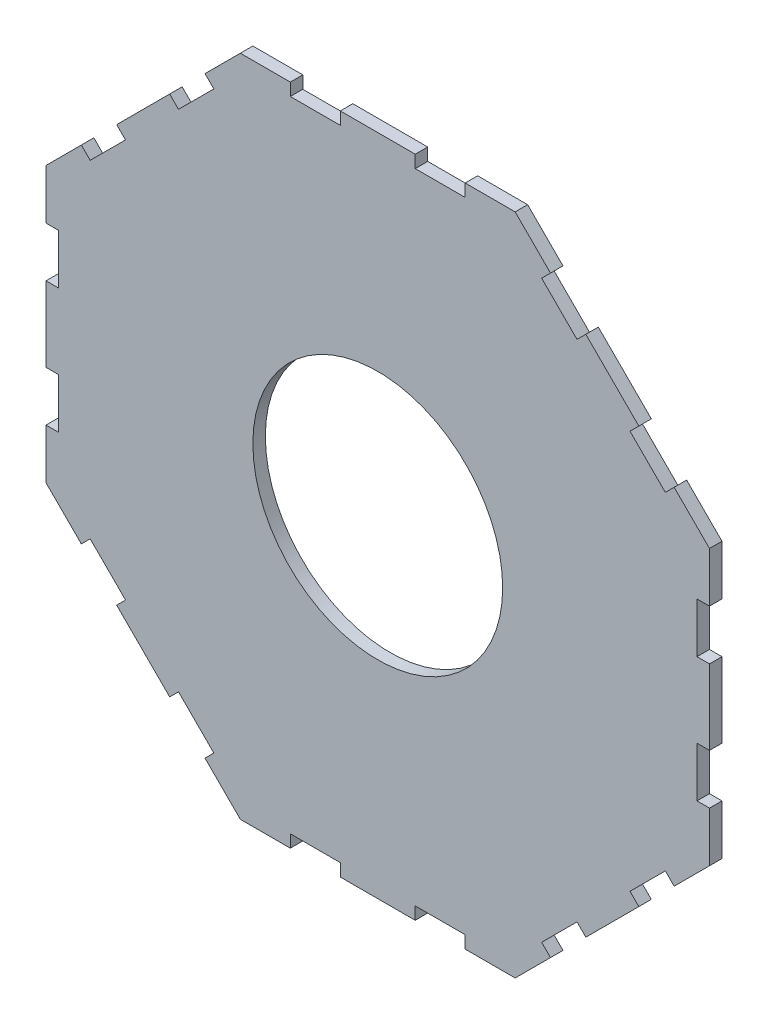
SolidWorks part; units mm, degrees
ref_plane "Front Plane" through (0, 0, 0) normal (0, 0, 1) x (1, 0, 0)
ref_plane "Top Plane" through (0, 0, 0) normal (0, 1, 0) x (1, 0, 0)
ref_plane "Right Plane" through (0, 0, 0) normal (1, 0, 0) x (0, 0, -1)
sketch "Sketch1" plane through (0, 0, 0) normal (0, 0, 1) x (1, 0, 0)
  line L0 (43.9053, 75.3362) -> (41.6602, 73.0911)
  line L1 (34.925, 84.3164) -> (-34.925, 84.3164)
  line L2 (-34.925, 84.3164) -> (-84.3164, 34.925)
  line L3 (-84.3164, 34.925) -> (-84.3164, -34.925)
  line L4 (-84.3164, -34.925) -> (-34.925, -84.3164)
  line L5 (-34.925, -84.3164) -> (34.925, -84.3164)
  line L6 (34.925, -84.3164) -> (84.3164, -34.925)
  line L7 (84.3164, -34.925) -> (84.3164, 34.925)
  line L8 (84.3164, 34.925) -> (34.925, 84.3164)
  line L9 (-22.225, 84.3164) -> (-9.525, 84.3164)
  line L10 (-22.225, 84.3164) -> (-22.225, 81.1414)
  line L11 (-22.225, 81.1414) -> (-9.525, 81.1414)
  line L12 (-9.525, 84.3164) -> (-9.525, 81.1414)
  line L13 (22.225, 84.3164) -> (9.525, 84.3164)
  line L14 (22.225, 84.3164) -> (22.225, 81.1414)
  line L15 (22.225, 81.1414) -> (9.525, 81.1414)
  line L16 (9.525, 84.3164) -> (9.525, 81.1414)
  line L17 (41.6602, 73.0911) -> (50.6404, 64.1108)
  line L18 (52.8855, 66.3559) -> (50.6404, 64.1108)
  line L19 (66.3559, 52.8855) -> (64.1108, 50.6404)
  line L20 (73.0911, 41.6602) -> (64.1108, 50.6404)
  line L21 (75.3362, 43.9053) -> (73.0911, 41.6602)
  line L22 (84.3164, 22.225) -> (81.1414, 22.225)
  line L23 (81.1414, 22.225) -> (81.1414, 9.525)
  line L24 (84.3164, 9.525) -> (81.1414, 9.525)
  line L25 (84.3164, -9.525) -> (81.1414, -9.525)
  line L26 (81.1414, -22.225) -> (81.1414, -9.525)
  line L27 (84.3164, -22.225) -> (81.1414, -22.225)
  line L28 (75.3362, -43.9053) -> (73.0911, -41.6602)
  line L29 (73.0911, -41.6602) -> (64.1108, -50.6404)
  line L30 (66.3559, -52.8855) -> (64.1108, -50.6404)
  line L31 (52.8855, -66.3559) -> (50.6404, -64.1108)
  line L32 (41.6602, -73.0911) -> (50.6404, -64.1108)
  line L33 (43.9053, -75.3362) -> (41.6602, -73.0911)
  line L34 (22.225, -84.3164) -> (22.225, -81.1414)
  line L35 (22.225, -81.1414) -> (9.525, -81.1414)
  line L36 (9.525, -84.3164) -> (9.525, -81.1414)
  line L37 (-9.525, -84.3164) -> (-9.525, -81.1414)
  line L38 (-22.225, -81.1414) -> (-9.525, -81.1414)
  line L39 (-22.225, -84.3164) -> (-22.225, -81.1414)
  line L40 (-43.9053, -75.3362) -> (-41.6602, -73.0911)
  line L41 (-41.6602, -73.0911) -> (-50.6404, -64.1108)
  line L42 (-52.8855, -66.3559) -> (-50.6404, -64.1108)
  line L43 (-66.3559, -52.8855) -> (-64.1108, -50.6404)
  line L44 (-73.0911, -41.6602) -> (-64.1108, -50.6404)
  line L45 (-75.3362, -43.9053) -> (-73.0911, -41.6602)
  line L46 (-84.3164, -22.225) -> (-81.1414, -22.225)
  line L47 (-81.1414, -22.225) -> (-81.1414, -9.525)
  line L48 (-84.3164, -9.525) -> (-81.1414, -9.525)
  line L49 (-84.3164, 9.525) -> (-81.1414, 9.525)
  line L50 (-81.1414, 22.225) -> (-81.1414, 9.525)
  line L51 (-84.3164, 22.225) -> (-81.1414, 22.225)
  line L52 (-75.3362, 43.9053) -> (-73.0911, 41.6602)
  line L53 (-73.0911, 41.6602) -> (-64.1108, 50.6404)
  line L54 (-66.3559, 52.8855) -> (-64.1108, 50.6404)
  line L55 (-52.8855, 66.3559) -> (-50.6404, 64.1108)
  line L56 (-41.6602, 73.0911) -> (-50.6404, 64.1108)
  line L57 (-43.9053, 75.3362) -> (-41.6602, 73.0911)
  circle A0 centre (0, 0) radius 84.3164 construction
  circle A1 centre (0, 0) radius 31.75
  point P78 (0, 0)
  point P79 (0, 0)
  dimension "D8" = 63.5
  dimension "D1" = 69.85
  dimension "D2" = 12.7
  dimension "D3" = 12.7
  dimension "D4" = 3.175
  dimension "D5" = 3.175
  dimension "D6" = 12.7
  dimension "D7" = 12.7
  dimension "D9" = 8
extrude "Boss-Extrude1" add sketch "Sketch1" along normal blind 3.175
